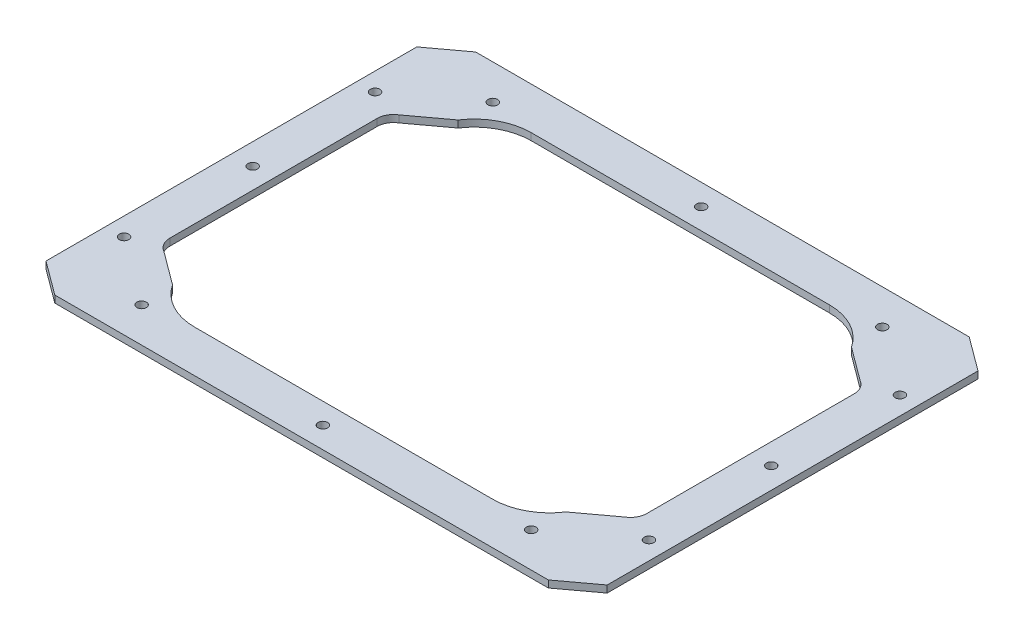
SolidWorks part; units mm, degrees
material "Thornel Mat VMA"
ref_plane "Front Plane" through (0, 0, 0) normal (0, 0, 1) x (1, 0, 0)
ref_plane "Top Plane" through (0, 0, 0) normal (0, 1, 0) x (1, 0, 0)
ref_plane "Right Plane" through (0, 0, 0) normal (1, 0, 0) x (0, 0, -1)
sketch "Sketch1" plane through (0, 0, 0) normal (0, 1, 0) x (1, 0, 0)
  line L0 (-127, 83.9186) -> (-111.6865, 95.25)
  line L1 (89.0238, 64.6231) -> (111.6865, 95.25) construction
  line L2 (104.3373, 53.2917) -> (127, 83.9186) construction
  line L3 (-127, 95.25) -> (127, 95.25)
  line L4 (127, 95.25) -> (0, 0) construction
  line L5 (-107.95, 46.9417) -> (-107.95, -46.9417)
  line L7 (127, -95.25) -> (127, 95.25)
  line L8 (104.3373, 53.2917) -> (89.0238, 64.6231)
  line L9 (127, 0) -> (-127, 0) construction
  line L10 (-127, 95.25) -> (0, 0) construction
  line L12 (107.95, 46.9417) -> (107.95, -46.9417)
  line L13 (127, 83.9186) -> (111.6865, 95.25)
  line L14 (-89.0238, -64.6231) -> (-111.6865, -95.25) construction
  line L15 (-104.3373, -53.2917) -> (-127, -83.9186) construction
  line L16 (-67.4905, -76.2) -> (67.4905, -76.2)
  line L17 (104.3373, -53.2917) -> (89.0238, -64.6231)
  line L18 (-127, -95.25) -> (127, -95.25)
  line L23 (0, -13.6985) -> (0, 95.25) construction
  line L27 (-104.3373, 53.2917) -> (-127, 83.9186) construction
  line L28 (-104.3373, 53.2917) -> (-89.0238, 64.6231)
  line L34 (-89.0238, 64.6231) -> (-111.6865, 95.25) construction
  line L36 (-67.4905, 76.2) -> (67.4905, 76.2)
  line L38 (-127, -95.25) -> (-127, 95.25)
  line L40 (0, 13.6985) -> (0, -95.25) construction
  line L41 (-127, -95.25) -> (0, 0) construction
  line L42 (127, -95.25) -> (0, 0) construction
  line L43 (104.3373, -53.2917) -> (127, -83.9186) construction
  line L44 (89.0238, -64.6231) -> (111.6865, -95.25) construction
  line L46 (-104.3373, -53.2917) -> (-89.0238, -64.6231)
  line L47 (127, -83.9186) -> (111.6865, -95.25)
  line L50 (-127, -83.9186) -> (-111.6865, -95.25)
  arc A0 (-67.4905, 76.2) -> (-89.0238, 64.6231) centre (-67.4905, 50.3855) ccw
  arc A1 (-107.95, 46.9417) -> (-104.3373, 53.2917) centre (-100.563, 46.9417) cw
  arc A2 (107.95, 46.9417) -> (104.3373, 53.2917) centre (100.563, 46.9417) ccw
  arc A3 (67.4905, 76.2) -> (89.0238, 64.6231) centre (67.4905, 50.3855) cw
  arc A4 (67.4905, -76.2) -> (89.0238, -64.6231) centre (67.4905, -50.3855) ccw
  arc A5 (107.95, -46.9417) -> (104.3373, -53.2917) centre (100.563, -46.9417) cw
  arc A6 (-107.95, -46.9417) -> (-104.3373, -53.2917) centre (-100.563, -46.9417) ccw
  arc A7 (-67.4905, -76.2) -> (-89.0238, -64.6231) centre (-67.4905, -50.3855) cw
  point P0 (0, 0)
  point P1 (0, 0)
  point P2 (107.95, 0)
  point P7 (0, 76.2)
  point P12 (-107.95, 0)
  point P14 (0, 0)
  point P16 (127, 0)
  point P17 (31.75, 0)
  point P18 (38.1, 0)
  point P22 (0, 76.2)
  point P32 (0, 76.2)
  point P33 (107.95, 0)
  point P35 (-89.0238, 76.2)
  point P36 (-107.95, 0)
  point P41 (0, 0)
  point P44 (-107.95, 0)
  point P45 (-38.1, 0)
  point P46 (-31.75, 0)
  point P51 (-107.95, 53.2917)
  point P54 (-107.95, -53.2917)
  point P57 (-89.0238, -76.2)
  point P60 (89.0238, -76.2)
  point P63 (89.0238, 76.2)
  point P66 (107.95, 53.2917)
  point P67 (-107.95, 0)
  point P68 (107.95, 0)
  point P69 (107.95, -53.2917)
  point P70 (0, -76.2)
  point P73 (107.95, 0)
  dimension "D8" = 19.05
  dimension "D9" = 19.05
  dimension "D1" = 254
  dimension "D2" = 190.5
  dimension "D3" = 19.05
  dimension "D4" = 134.9811
  dimension "D10" = 19.05
  dimension "D11" = 19.05
  dimension "D5" = 143.5
  dimension "D6" = 19.05
  dimension "D7" = 38.1
extrude "Boss-Extrude1" add sketch "Sketch1" along normal blind 3.175
sketch "Sketch2" plane through (0, 3.175, 0) normal (0, 1, 0) x (1, 0, 0)
  line L0 (-96.6805, 58.9574) -> (-119.3433, 89.5843) construction
  line L1 (-104.3373, 53.2917) -> (-89.0238, 64.6231) construction
  line L2 (-127, 83.9186) -> (-111.6865, 95.25) construction
  line L3 (0, 0) -> (0, 95.25) construction
  line L4 (-111.6865, 95.25) -> (111.6865, 95.25) construction
  line L5 (-127, 0) -> (0, 0) construction
  line L11 (-127, 83.9186) -> (-111.6865, 95.25) construction
  line L12 (-127, -83.9186) -> (-127, 83.9186) construction
  line L13 (-111.6865, -95.25) -> (111.6865, -95.25) construction
  circle A0 centre (-88.1548, 79.4619) radius 2.159
  circle A1 centre (88.1548, 79.4619) radius 2.159
  circle A2 centre (88.1548, -79.4619) radius 2.159
  circle A3 centre (-88.1548, -79.4619) radius 2.159
  circle A4 centre (-118.7817, 56.7991) radius 2.159
  circle A5 centre (118.7817, 56.7991) radius 2.159
  circle A6 centre (-118.7817, -56.7991) radius 2.159
  circle A7 centre (118.7817, -56.7991) radius 2.159
  circle A8 centre (0, -85.598) radius 2.159
  circle A9 centre (0, 85.598) radius 2.159
  circle A10 centre (-117.348, -0.0205) radius 2.159
  circle A11 centre (117.348, -0.0205) radius 2.159
  dimension "D2" = 4.318
  dimension "D3" = 9.652
  dimension "D1" = 19.05
  dimension "D4" = 9.652
  dimension "D5" = 127
  dimension "D7" = 127
  dimension "D8" = 26.6886
extrude "Cut-Extrude1" cut sketch "Sketch2" against normal through all
